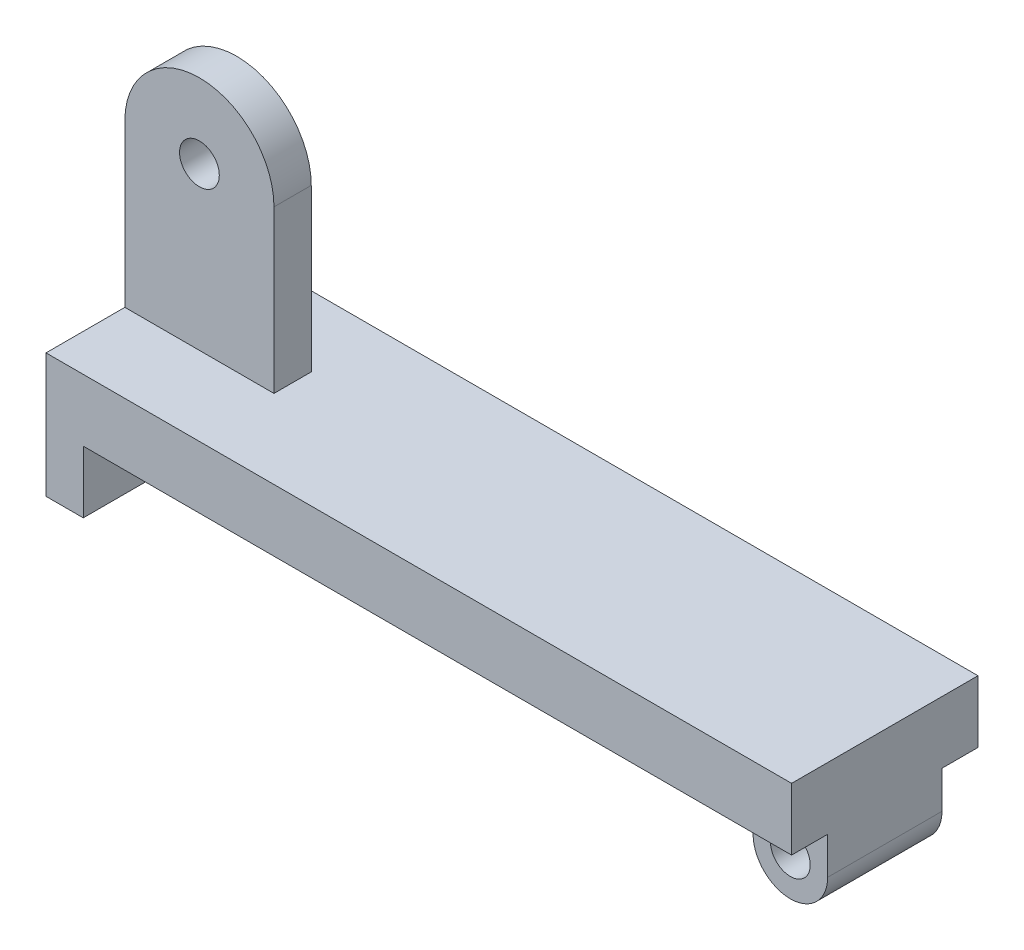
SolidWorks part; units mm, degrees
ref_plane "前视基准面" through (0, 0, 0) normal (0, 0, 1) x (1, 0, 0)
ref_plane "上视基准面" through (0, 0, 0) normal (0, 1, 0) x (1, 0, 0)
ref_plane "右视基准面" through (0, 0, 0) normal (1, 0, 0) x (0, 0, -1)
sketch "草图1" plane through (0, 0, 0) normal (0, 1, 0) x (1, 0, 0)
  line L13 (-31.6231, 13.5019) -> (28.3769, 13.5019)
  line L14 (-31.6231, 13.5019) -> (-31.6231, -1.4981)
  line L15 (-31.6231, -1.4981) -> (28.3769, -1.4981)
  line L16 (28.3769, 13.5019) -> (28.3769, -1.4981)
  dimension "D1" = 60
  dimension "D2" = 15
extrude "凸台-拉伸1" add sketch "草图1" along normal blind 5
sketch "草图2" plane through (0, 0, 0) normal (0, -1, 0) x (1, 0, 0)
  line L0 (28.3769, -13.5019) -> (-31.6231, -13.5019) construction
  line L1 (-31.6231, 1.4981) -> (-28.6231, 1.4981)
  line L2 (-31.6231, 1.4981) -> (-31.6231, -13.5019)
  line L3 (-31.6231, -13.5019) -> (-28.6231, -13.5019)
  line L4 (-28.6231, 1.4981) -> (-28.6231, -13.5019)
  dimension "D1" = 3
extrude "凸台-拉伸2" add sketch "草图2" along normal blind 5
sketch "草图3" plane through (0, 0, 0) normal (0, -1, 0) x (1, 0, 0)
  line L0 (28.3769, 1.4981) -> (28.3769, -13.5019) construction
  line L1 (22.3769, -1.0019) -> (28.3769, -1.0019)
  line L2 (22.3769, -1.0019) -> (22.3769, -11.0019)
  line L3 (22.3769, -11.0019) -> (28.3769, -11.0019)
  line L4 (28.3769, -1.0019) -> (28.3769, -11.0019)
  point P6 (22.3769, -6.0019)
  point P7 (28.3769, -6.0019)
  dimension "D1" = 6
  dimension "D2" = 10
extrude "凸台-拉伸3" add sketch "草图3" along normal blind 6
sketch "草图4" plane through (0, 0, -1.0019) normal (0, 0, 1) x (1, 0, 0)
  line L0 (22.3769, -3) -> (22.3769, -6)
  line L2 (22.3769, 0) -> (22.3769, -6) construction
  line L3 (22.3769, -6) -> (28.3769, -6) construction
  line L4 (28.3769, 0) -> (28.3769, -6) construction
  line L5 (22.3769, -6) -> (28.3769, -6)
  line L6 (28.3769, -6) -> (28.3769, -3)
  arc A1 (22.3769, -3) -> (28.3769, -3) centre (25.3769, -3) ccw
  point P6 (25.3769, 0)
  point P7 (25.3769, -6)
  point P8 (22.3769, -3)
  point P9 (28.3769, -3)
  line M2 (22.3769, 0) -> (22.3769, -6)
  line M3 (22.3769, -6) -> (28.3769, -6)
  line M4 (28.3769, -6) -> (28.3769, 0)
extrude "切除-拉伸1" cut sketch "草图4" against normal blind 20 contours A1 L5 M4 | A1 M2 M3
sketch "草图5" plane through (0, 0, -1.0019) normal (0, 0, 1) x (1, 0, 0)
  line L0 (22.3769, -3) -> (22.3769, 0) construction
  line L1 (28.3769, -3) -> (28.3769, 0) construction
  line L3 (22.3769, -2.841) -> (28.3769, -2.841) construction
  circle A0 centre (25.3769, -2.841) radius 1.6
  point P4 (25.3769, -2.841)
  dimension "D1" = 6
extrude "切除-拉伸2" cut sketch "草图5" against normal blind 20
sketch "草图6" plane through (0, 5, 0) normal (0, 1, 0) x (1, 0, 0)
  line L0 (-25.6231, 14.4082) -> (-25.6231, -0.5918) construction
  line L3 (-35.8491, 6.3474) -> (-23.1313, 6.3474) construction
  line L5 (-31.6231, 13.5019) -> (-31.6231, -1.4981) construction
  line L6 (-31.6231, 8.2474) -> (-19.6231, 8.2474)
  line L7 (-31.6231, 8.2474) -> (-31.6231, 4.4474)
  line L8 (-31.6231, 4.4474) -> (-19.6231, 4.4474)
  line L9 (-19.6231, 8.2474) -> (-19.6231, 4.4474)
  point P5 (-31.6231, 6.3474)
  point P8 (-25.6231, 8.2474)
  dimension "D1" = 3.8
  dimension "D2" = 12
  dimension "D3" = 6
extrude "凸台-拉伸5" add sketch "草图6" along normal blind 19
sketch "草图10" plane through (0, 0, -4.4474) normal (0, 0, 1) x (1, 0, 0)
  line L0 (-19.6231, 24) -> (-19.6231, 5) construction
  line L1 (-31.6231, 24) -> (-19.6231, 24) construction
  line L2 (-31.6231, 24) -> (-31.6231, 12) construction
  line L3 (-31.6231, 12) -> (-19.6231, 12) construction
  line L4 (-19.6231, 24) -> (-19.6231, 12) construction
  line L5 (-31.6231, 24) -> (-19.6231, 12) construction
  circle A0 centre (-25.6231, 18) radius 1.6
  point P7 (-25.6231, 18)
  dimension "D1" = 12
extrude "切除-拉伸4" cut sketch "草图10" against normal blind 19
sketch "草图11" plane through (0, 0, -4.4474) normal (0, 0, 1) x (1, 0, 0)
  line L0 (-19.6231, 24) -> (-19.6231, 5) construction
  line L1 (-31.6231, 24) -> (-19.6231, 24) construction
  line L2 (-31.6231, 24) -> (-31.6231, 12) construction
  line L3 (-31.6231, 12) -> (-19.6231, 12) construction
  line L4 (-19.6231, 24) -> (-19.6231, 12) construction
  line L5 (-31.6231, 18) -> (-31.6231, 24)
  line L6 (-31.6231, 24) -> (-19.6231, 24)
  line L7 (-19.6231, 24) -> (-19.6231, 18)
  arc A0 (-31.6231, 18) -> (-19.6231, 18) centre (-25.6231, 18) cw
  point P7 (-31.6231, 18)
  point P8 (-25.6231, 18)
  point P9 (-19.6231, 18)
  point P11 (-25.6231, 24)
  line M8 (-19.6231, 5) -> (-19.6231, 24)
  line M9 (-19.6231, 24) -> (-31.6231, 24)
  line M10 (-31.6231, 24) -> (-31.6231, 5)
  dimension "D1" = 12
extrude "切除-拉伸5" cut sketch "草图11" against normal blind 19 contours A0 L6 M10 | A0 M9 M8
sketch "草图12" plane through (0, 0, -4.4474) normal (0, 0, 1) x (1, 0, 0)
  line L0 (-19.6231, 18) -> (-19.6231, 5) construction
  line L1 (-31.6231, 5) -> (-19.6231, 5)
  line L2 (-31.6231, 5) -> (-31.6231, 24)
  line L3 (-31.6231, 24) -> (-19.6231, 24)
  line L4 (-19.6231, 5) -> (-19.6231, 24)
  line L5 (-31.6231, 5) -> (-19.6231, 24) construction
  line L6 (-31.6231, 24) -> (-19.6231, 5) construction
  arc A0 (-19.6231, 18) -> (-31.6231, 18) centre (-25.6231, 18) ccw construction
  point P4 (-25.6231, 14.5)
extrude "切除-拉伸6" cut sketch "草图12" against normal blind 0.4
sketch "草图13" plane through (0, 0, -8.2474) normal (0, 0, -1) x (-1, 0, 0)
  line L0 (31.6231, 18) -> (31.6231, 5) construction
  line L1 (19.6231, 5) -> (31.6231, 5)
  line L2 (19.6231, 5) -> (19.6231, 24)
  line L3 (19.6231, 24) -> (31.6231, 24)
  line L4 (31.6231, 5) -> (31.6231, 24)
  line L5 (19.6231, 5) -> (31.6231, 24) construction
  line L6 (19.6231, 24) -> (31.6231, 5) construction
  arc A0 (31.6231, 18) -> (19.6231, 18) centre (25.6231, 18) ccw construction
  point P4 (25.6231, 14.5)
extrude "切除-拉伸7" cut sketch "草图13" against normal blind 0.4
sketch "草图14" plane through (0, 0, -11.0019) normal (0, 0, -1) x (-1, 0, 0)
  line L0 (-22.3769, -3) -> (-22.3769, 0) construction
  line L1 (-28.3769, 0) -> (-22.3769, 0)
  line L2 (-28.3769, 0) -> (-28.3769, -6)
  line L3 (-28.3769, -6) -> (-22.3769, -6)
  line L4 (-22.3769, 0) -> (-22.3769, -6)
  line L5 (-28.3769, 0) -> (-22.3769, -6) construction
  line L6 (-28.3769, -6) -> (-22.3769, 0) construction
  arc A0 (-28.3769, -3) -> (-22.3769, -3) centre (-25.3769, -3) ccw construction
  point P4 (-25.3769, -3)
extrude "切除-拉伸8" cut sketch "草图14" against normal blind 0.4
sketch "草图15" plane through (0, 0, -1.0019) normal (0, 0, 1) x (1, 0, 0)
  line L0 (28.3769, -3) -> (28.3769, 0) construction
  line L1 (22.3769, 0) -> (28.3769, 0)
  line L2 (22.3769, 0) -> (22.3769, -6)
  line L3 (22.3769, -6) -> (28.3769, -6)
  line L4 (28.3769, 0) -> (28.3769, -6)
  line L5 (22.3769, 0) -> (28.3769, -6) construction
  line L6 (22.3769, -6) -> (28.3769, 0) construction
  arc A0 (22.3769, -3) -> (28.3769, -3) centre (25.3769, -3) ccw construction
  point P4 (25.3769, -3)
extrude "切除-拉伸9" cut sketch "草图15" against normal blind 0.4
